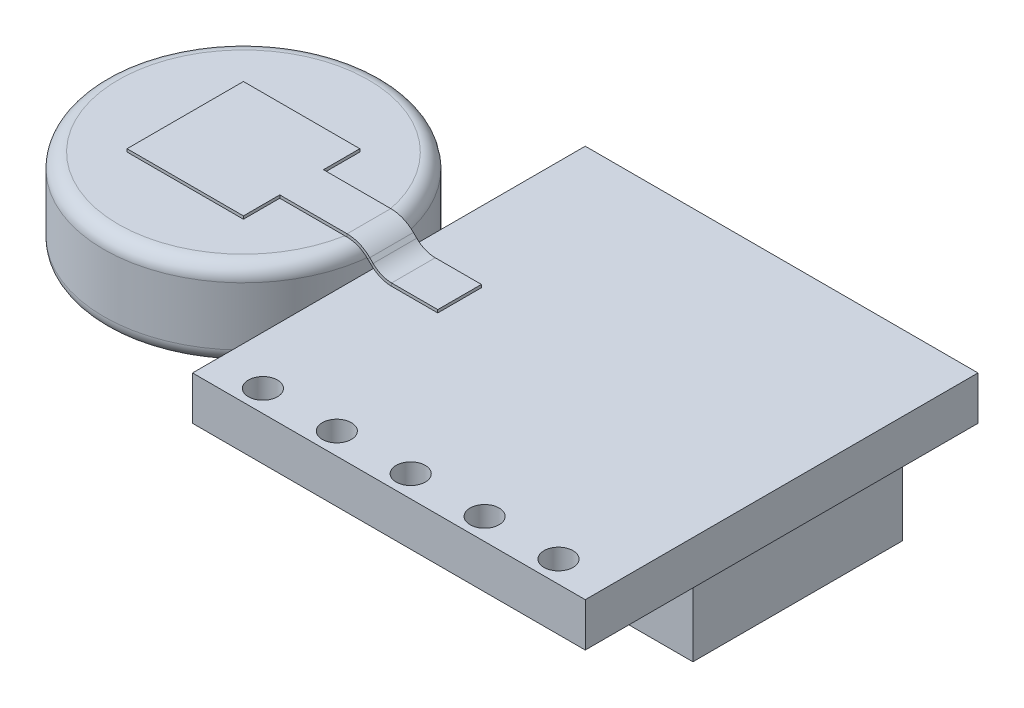
SolidWorks part; units mm, degrees
ref_plane "Front Plane" through (0, 0, 0) normal (0, 0, 1) x (1, 0, 0)
ref_plane "Top Plane" through (0, 0, 0) normal (0, 1, 0) x (1, 0, 0)
ref_plane "Right Plane" through (0, 0, 0) normal (1, 0, 0) x (0, 0, -1)
sketch "Sketch1" plane through (0, 0, 0) normal (0, 1, 0) x (1, 0, 0)
  line L1 (0, 0) -> (13.5, 0)
  line L2 (0, 0) -> (0, 13.5)
  line L3 (0, 13.5) -> (13.5, 13.5)
  line L4 (13.5, 0) -> (13.5, 13.5)
  dimension "D1" = 13.5
  dimension "D2" = 13.5
extrude "Boss-Extrude1" add sketch "Sketch1" along normal blind 1.5 contours L2 L3 L4 L1
sketch "Sketch2" plane through (0, 1.5, 0) normal (0, 1, 0) x (1, 0, 0)
  line L0 (13.5, 0) -> (13.5, 13.5) construction
  line L1 (0, 0) -> (13.5, 0) construction
  circle A0 centre (11.83, 0.75) radius 0.5
  circle A1 centre (9.29, 0.75) radius 0.5
  circle A2 centre (6.75, 0.75) radius 0.5
  circle A3 centre (4.21, 0.75) radius 0.5
  circle A4 centre (1.67, 0.75) radius 0.5
  dimension "D1" = 1
  dimension "D3" = 1.67
  dimension "D4" = 0.75
  dimension "D2" = 5
extrude "Cut-Extrude1" cut sketch "Sketch2" against normal blind 1.5
sketch "Sketch3" plane through (0, 0, 0) normal (0, 1, 0) x (1, 0, 0)
  line L0 (0, 13.5) -> (13.5, 13.5) construction
  line L1 (0, 0) -> (0, 13.5) construction
  circle A0 centre (-5, 6.75) radius 4.8
  dimension "D1" = 9.6
  dimension "D2" = 6.75
  dimension "D3" = 5
extrude "Boss-Extrude2" add sketch "Sketch3" against normal blind 0.8 separate body
sketch "Sketch4" plane through (0, 0, 0) normal (0, 1, 0) x (1, 0, 0)
  circle A1 centre (-5, 6.75) radius 4.8
  circle A2 centre (-5, 6.75) radius 4.8
  dimension "D1" = 0
extrude "Boss-Extrude3" add sketch "Sketch4" along normal blind 2.2
fillet "Fillet1" radius 0.5 2 edges at (-5, -0.8, -1.95) (-5, 2.2, -1.95)
sketch "Sketch5" plane through (0, 0, 0) normal (0, -1, 0) x (1, 0, 0)
  line L0 (0, -13.5) -> (13.5, -13.5) construction
  line L1 (13, -4.2) -> (2.6, -4.2)
  line L2 (13, -4.2) -> (13, -11.4)
  line L3 (13, -11.4) -> (2.6, -11.4)
  line L4 (2.6, -4.2) -> (2.6, -11.4)
  line L5 (13.5, 0) -> (13.5, -13.5) construction
  dimension "D1" = 10.4
  dimension "D2" = 7.2
  dimension "D3" = 2.1
  dimension "D4" = 0.5
extrude "Boss-Extrude4" add sketch "Sketch5" along normal blind 2.7
ref_plane "Plane1" through (-3, 0, 0) normal (1, 0, 0) x (0, 0, -1)
ref_plane "Plane2" through (0, 0, -6.75) normal (0, 0, 1) x (1, 0, 0)
sketch "Sketch6" plane through (0, 0, -6.75) normal (0, 0, 1) x (1, 0, 0)
  line L0 (-3, 2.2) -> (-0.6847, 2.2)
  line L1 (-3, -2.75) -> (-3, 2.75) construction
  line L2 (-0.7, 2.2) -> (-9.3, 2.2) construction
  line L3 (0.0224, 1.9071) -> (0.1366, 1.7929)
  line L4 (0, 1.5) -> (13.5, 1.5) construction
  line L5 (0.8437, 1.5) -> (2.4295, 1.5)
  arc A0 (0.1366, 1.7929) -> (0.8437, 1.5) centre (0.8437, 2.5) ccw
  arc A1 (-0.6847, 2.2) -> (0.0224, 1.9071) centre (-0.6847, 1.2) cw
  point P12 (0.4295, 1.5)
  dimension "D2" = 1
  dimension "D1" = 2
sketch "Sketch7" plane through (-3, 0, 0) normal (1, 0, 0) x (0, 0, -1)
  line L0 (11.05, 2.2) -> (2.45, 2.2) construction
  line L1 (6, 2.2) -> (7.5, 2.2)
  line L2 (6, 2.2) -> (6, 2.3)
  line L3 (6, 2.3) -> (7.5, 2.3)
  line L4 (7.5, 2.2) -> (7.5, 2.3)
  line L5 (6.75, 2.695) -> (6.75, -2.695) construction
  dimension "D1" = 1.5
  dimension "D2" = 0.75
  dimension "D3" = 0.1
sweep "Sweep1" add profiles "Sketch7" path "Sketch6"
sketch "Sketch8" plane through (-3, 0, 0) normal (1, 0, 0) x (0, 0, -1)
  line L0 (11.05, 2.2) -> (2.45, 2.2) construction
  line L1 (4.75, 2.2) -> (8.75, 2.2)
  line L2 (4.75, 2.2) -> (4.75, 2.3)
  line L3 (4.75, 2.3) -> (8.75, 2.3)
  line L4 (8.75, 2.2) -> (8.75, 2.3)
  line L5 (7.5, 1.9778) -> (7.5, 2.3) construction
  dimension "D1" = 0.1
  dimension "D2" = 4
  dimension "D3" = 1.25
extrude "Boss-Extrude5" add sketch "Sketch8" against normal blind 4
